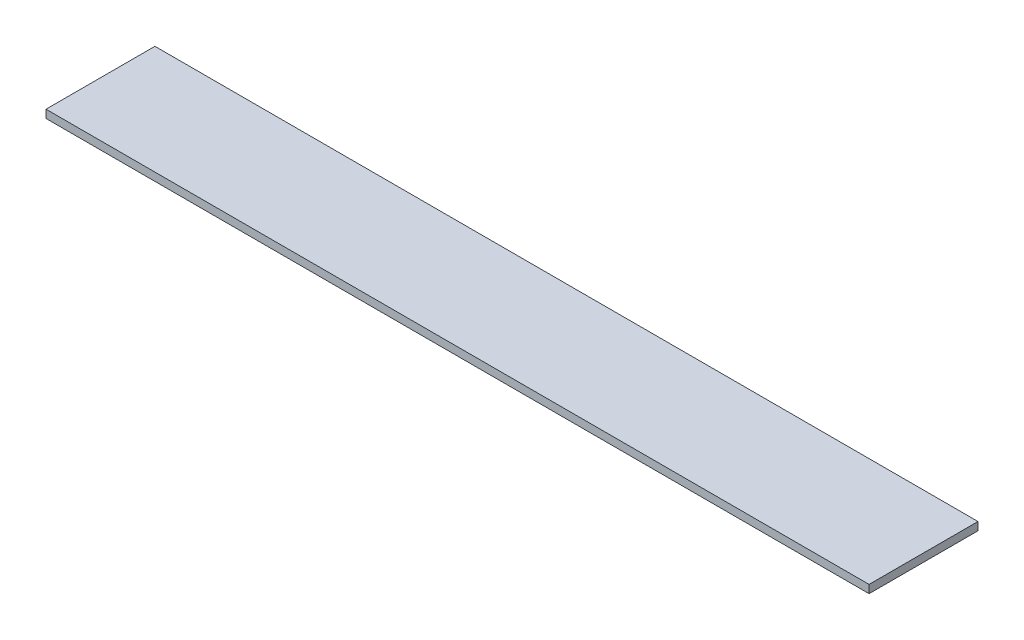
SolidWorks part; units mm, degrees
ref_plane "Front" through (0, 0, 0) normal (0, 0, 1) x (1, 0, 0)
ref_plane "Top" through (0, 0, 0) normal (0, 1, 0) x (1, 0, 0)
ref_plane "Right" through (0, 0, 0) normal (1, 0, 0) x (0, 0, -1)
sketch "Эскиз1" plane through (0, 0, 0) normal (0, 1, 0) x (1, 0, 0)
  line L1 (-6, 456) -> (606, 456)
  line L2 (-6, 456) -> (-6, 375)
  line L3 (-6, 375) -> (606, 375)
  line L4 (606, 456) -> (606, 375)
  point P4 (0, 0)
  point P5 (0, 0)
  dimension "D1" = 81
  dimension "D2" = 612
extrude "Бобышка-Вытянуть1" add sketch "Эскиз1" along normal blind 6
